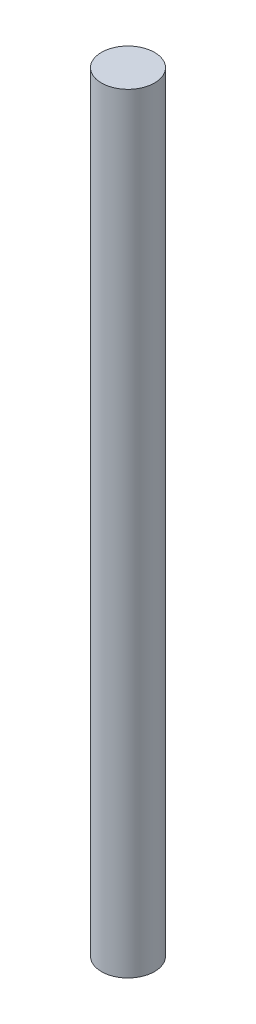
SolidWorks part; units mm, degrees
material "Pine"
ref_plane "Front" through (0, 0, 0) normal (0, 0, 1) x (1, 0, 0)
ref_plane "Top" through (0, 0, 0) normal (0, 1, 0) x (1, 0, 0)
ref_plane "Right" through (0, 0, 0) normal (1, 0, 0) x (0, 0, -1)
sketch "Sketch1" plane through (0, 0, 0) normal (0, 1, 0) x (1, 0, 0)
  circle A0 centre (0, 0) radius 5
  dimension "D1" = 10
extrude "Boss-Extrude1" add sketch "Sketch1" along normal blind 145
